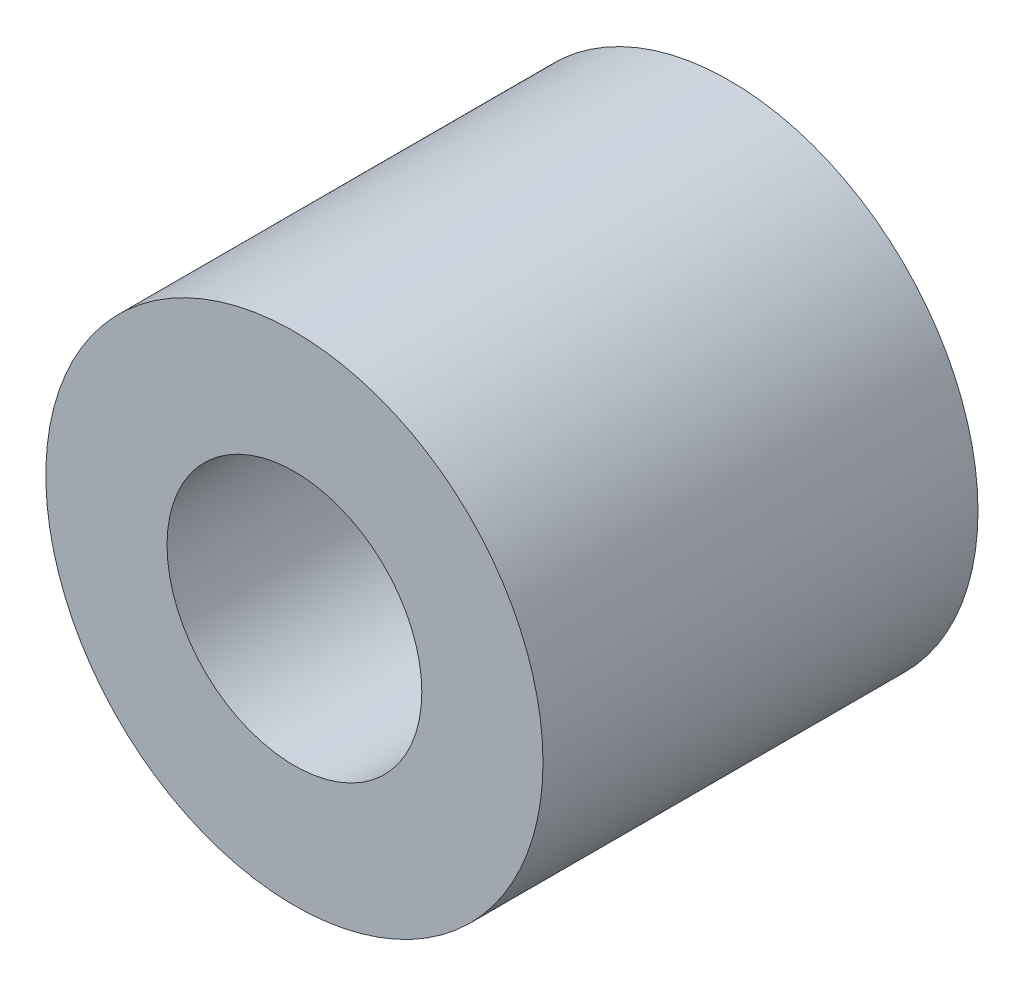
SolidWorks part; units mm, degrees
ref_plane "Front Plane" through (0, 0, 0) normal (0, 0, 1) x (1, 0, 0)
ref_plane "Top Plane" through (0, 0, 0) normal (0, 1, 0) x (1, 0, 0)
ref_plane "Right Plane" through (0, 0, 0) normal (1, 0, 0) x (0, 0, -1)
sketch "Sketch1" plane through (0, 0, 0) normal (0, 0, 1) x (1, 0, 0)
  circle A0 centre (0, 0) radius 2.05
  circle A1 centre (0, 0) radius 4
  dimension "D1" = 4.1
  dimension "D2" = 8
extrude "Boss-Extrude1" add sketch "Sketch1" along normal blind 7
